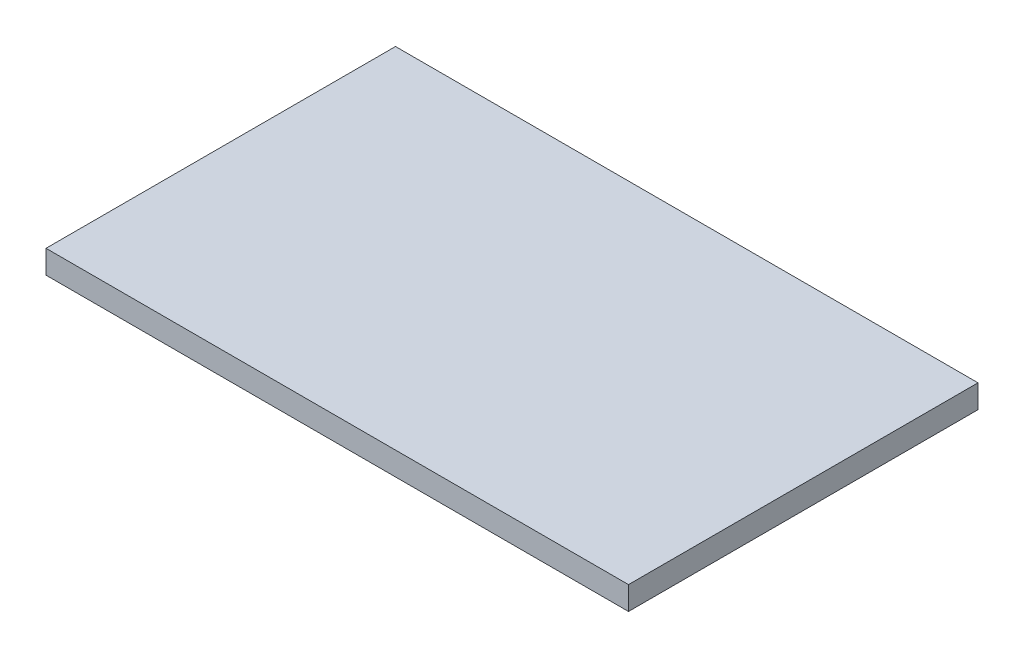
SolidWorks part; units mm, degrees
ref_plane "Front Plane" through (0, 0, 0) normal (0, 0, 1) x (1, 0, 0)
ref_plane "Top Plane" through (0, 0, 0) normal (0, 1, 0) x (1, 0, 0)
ref_plane "Right Plane" through (0, 0, 0) normal (1, 0, 0) x (0, 0, -1)
sketch "Sketch1" plane through (0, 0, 0) normal (0, 1, 0) x (1, 0, 0)
  line L1 (-100, -60) -> (100, -60)
  line L2 (-100, -60) -> (-100, 60)
  line L3 (-100, 60) -> (100, 60)
  line L4 (100, -60) -> (100, 60)
  line L5 (-100, -60) -> (100, 60) construction
  line L6 (-100, 60) -> (100, -60) construction
  point P0 (0, 0)
  dimension "D1" = 120
  dimension "D2" = 200
extrude "Boss-Extrude1" add sketch "Sketch1" along normal mid plane 8
